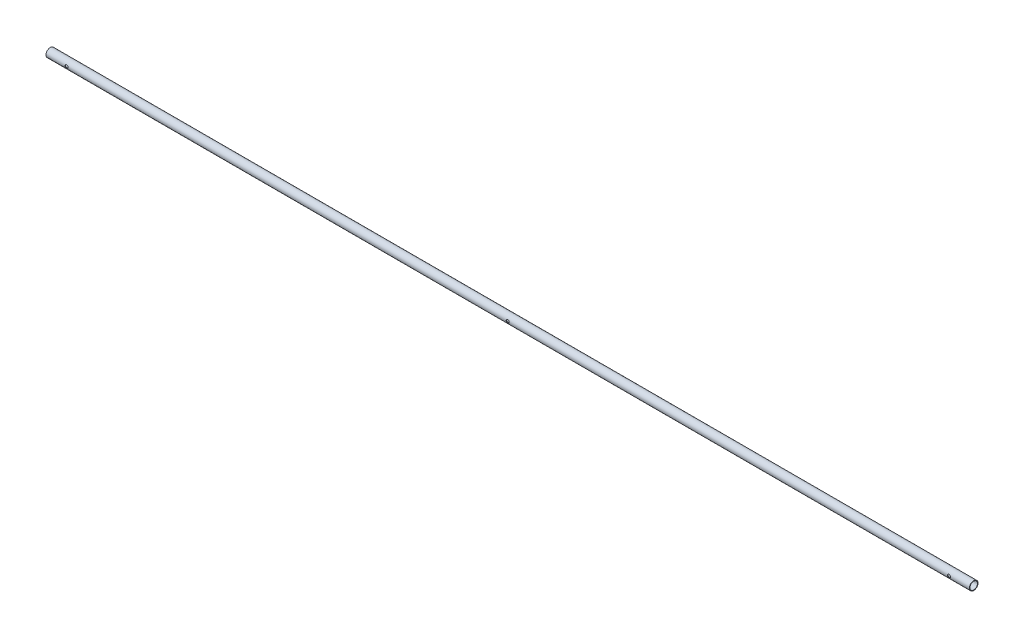
SolidWorks part; units mm, degrees
material "Galvanized Steel"
ref_plane "Front Plane" through (0, 0, 0) normal (0, 0, 1) x (1, 0, 0)
ref_plane "Top Plane" through (0, 0, 0) normal (0, 1, 0) x (1, 0, 0)
ref_plane "Right Plane" through (0, 0, 0) normal (1, 0, 0) x (0, 0, -1)
sketch "Sketch1" plane through (0, 0, 0) normal (1, 0, 0) x (0, 0, -1)
  circle A0 centre (0, 0) radius 7.8994
  circle A1 centre (0, 0) radius 8.9662
  dimension "D1" = 15.7988
  dimension "D2" = 17.9324
extrude "Boss-Extrude1" add sketch "Sketch1" along normal blind 1930.4
sketch "Sketch2" plane through (0, 0, 0) normal (0, 0, 1) x (1, 0, 0)
  line L1 (0, 8.9662) -> (0, -8.9662) construction
  line L3 (1930.4, -8.9662) -> (1930.4, 8.9662) construction
  circle A0 centre (965.2, 0) radius 3.175
  circle A4 centre (1887.5908, 0) radius 3.175
  circle A6 centre (42.8092, 0) radius 3.175
  dimension "D1" = 42.8092
  dimension "D3" = 922.3908
  dimension "D4" = 922.3908
  dimension "D2" = 965.2
  dimension "D5" = 42.8092
extrude "Cut-Extrude1" cut sketch "Sketch2" against normal through all and the other way through all
equation "\"extrudelength\"=76"
equation "\"D1@Boss-Extrude1\"=\"extrudelength\""
equation "\"D2@Sketch2\"=\"extrudelength\"/2"
